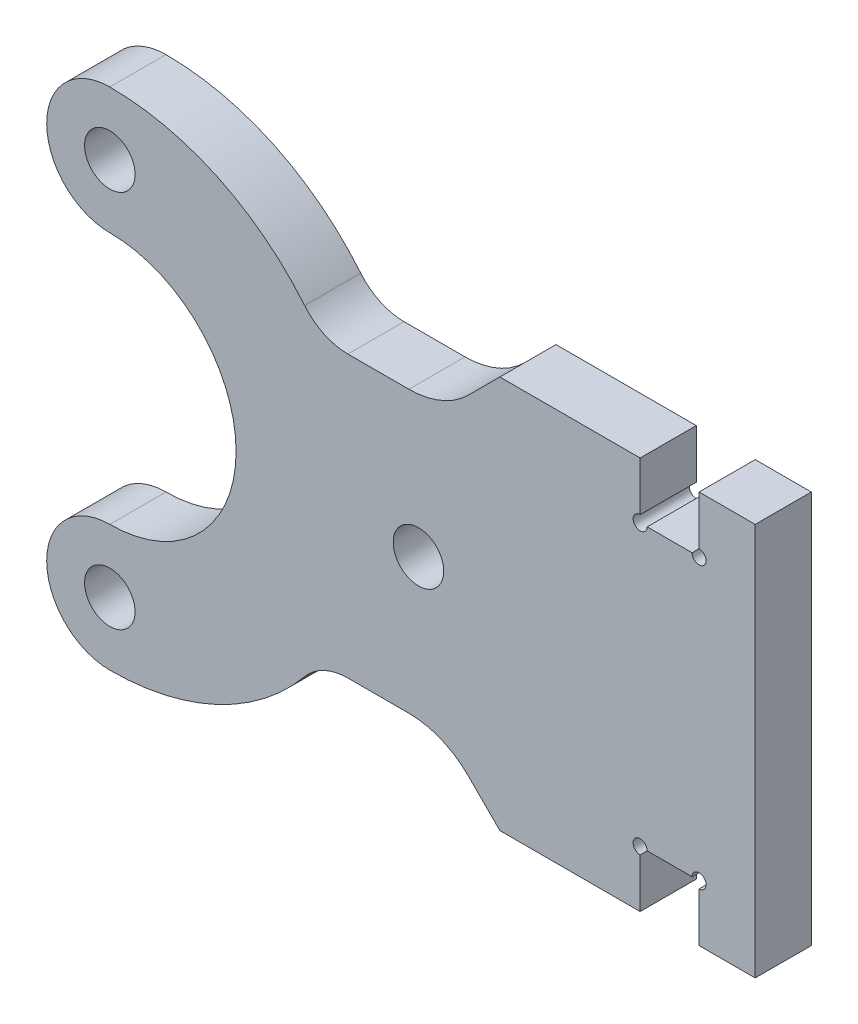
SolidWorks part; units mm, degrees
ref_plane "前视基准面" through (0, 0, 0) normal (0, 0, 1) x (1, 0, 0)
ref_plane "上视基准面" through (0, 0, 0) normal (0, 1, 0) x (1, 0, 0)
ref_plane "右视基准面" through (0, 0, 0) normal (1, 0, 0) x (0, 0, -1)
sketch "草图1" plane through (0, 0, 0) normal (0, 0, 1) x (1, 0, 0)
  line L0 (0, 0) -> (26.7626, 0) construction
  line L1 (8.4853, -5) -> (10.6574, -5)
  line L2 (8.4853, 5) -> (10.6574, 5)
  line L3 (0, 5) -> (25, 5) construction
  line L4 (0, -5) -> (25, -5) construction
  line L5 (23, 7) -> (23, -7)
  line L6 (23, 7) -> (21, 7)
  line L7 (21, 7) -> (21, 5.25)
  line L8 (0, 0) -> (25, 0) construction
  line L9 (23, -7) -> (21, -7)
  line L10 (21, -7) -> (21, -5.25)
  line L11 (18.9, 5.25) -> (18.9, 7)
  line L12 (18.9, 7) -> (13.9, 7)
  line L13 (13.9, 7) -> (12.7787, 5.8787)
  line L14 (13.9, -7) -> (12.7787, -5.8787)
  line L15 (18.9, -7) -> (13.9, -7)
  line L16 (18.9, -5.25) -> (18.9, -7)
  line L17 (19.15, 5) -> (20.75, 5)
  line L18 (19.15, -5) -> (20.75, -5)
  arc A0 (6.9425, 5.7273) -> (0, 9) centre (0, 0) ccw
  arc A1 (20.75, 5) -> (21, 5.25) centre (21, 5) ccw
  circle A2 centre (0, 6.75) radius 0.9
  circle A3 centre (0, -6.75) radius 0.9
  arc A4 (0, 9) -> (0, 4.5) centre (0, 6.75) ccw
  circle A5 centre (11, 0) radius 0.9
  arc A6 (0, -4.5) -> (0, -9) centre (0, -6.75) ccw
  arc A7 (0, 4.5) -> (0, -4.5) centre (0, 0) cw
  arc A8 (8.4853, -5) -> (6.9425, -5.7273) centre (8.4853, -7) ccw
  arc A9 (0, -9) -> (6.9425, -5.7273) centre (0, 0) ccw
  arc A10 (8.4853, 5) -> (6.9425, 5.7273) centre (8.4853, 7) cw
  arc A11 (18.9, 5.25) -> (19.15, 5) centre (18.9, 5) ccw
  arc A12 (19.15, -5) -> (18.9, -5.25) centre (18.9, -5) ccw
  arc A13 (21, -5.25) -> (20.75, -5) centre (21, -5) ccw
  arc A14 (12.7787, -5.8787) -> (10.6574, -5) centre (10.6574, -8) ccw
  arc A15 (12.7787, 5.8787) -> (10.6574, 5) centre (10.6574, 8) cw
  point P32 (7.4833, 5)
  point P55 (11.9, -5)
  point P58 (11.9, 5)
  dimension "D3" = 1.8
  dimension "D4" = 1.8
  dimension "D6" = 4.5
  dimension "D8" = 9
  dimension "D9" = 2
  dimension "D7" = 11
  dimension "D18" = 0.5
  dimension "D19" = 3
  dimension "D20" = 1.8
  dimension "D5" = 13.5
  dimension "D10" = 23
  dimension "D11" = 2
  dimension "D12" = 14
  dimension "D13" = 2.1
  dimension "D14" = 2
  dimension "D15" = 2
  dimension "D16" = 45
  dimension "D17" = 5
  dimension "D1" = 5
  dimension "D2" = 5
extrude "凸台-拉伸1" add sketch "草图1" along normal blind 2
